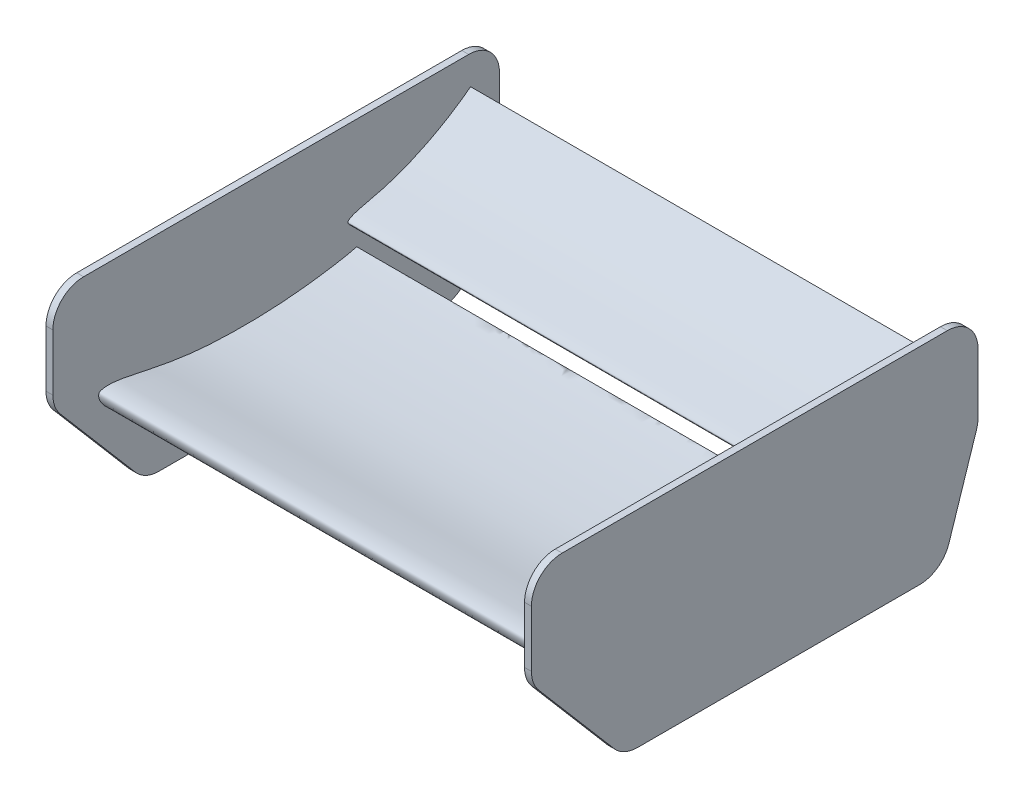
SolidWorks part; units mm, degrees
ref_plane "Front Plane" through (0, 0, 0) normal (0, 0, 1) x (1, 0, 0)
ref_plane "Top Plane" through (0, 0, 0) normal (0, 1, 0) x (1, 0, 0)
ref_plane "Right Plane" through (0, 0, 0) normal (1, 0, 0) x (0, 0, -1)
ref_plane "Soft Top Limit" through (0, 1174.6, 0) normal (0, 1, 0) x (1, 0, 0)
ref_plane "Soft Rear Limit" through (0, 0, -1192.975) normal (0, 0, 1) x (1, 0, 0)
ref_plane "Soft Right Limit" through (-501.65, 0, 0) normal (1, 0, 0) x (0, 0, -1)
ref_plane "Soft Left Limit" through (501.65, 0, 0) normal (1, 0, 0) x (0, 0, -1)
ref_plane "Soft Front Limit" through (0, 0, -165.1) normal (0, 0, 1) x (1, 0, 0)
ref_plane "Slant Limit" through (0, 528.6251, -619.2711) normal (0, -0.6492, 0.7606) x (1, 0, 0)
ref_plane "Bottom" through (0, 476.25, 0) normal (0, 1, 0) x (1, 0, 0)
ref_plane "Midplane" through (0, 0, 0) normal (1, 0, 0) x (0, 0, -1)
curve "Imported Airfoil Curve"
  spline degree 3 poles (0, 2520.0207, 6.126) (0, 2544.889, -1.81) (0, 2521.8965, 7.8839) (0, 2505.3253, 17.7145) (0, 2467.7144, 38.5723) (0, 2424.2142, 62.3813) (0, 2368.0949, 87.8078) (0, 2301.3729, 113.3478) (0, 2223.8362, 140.5377) (0, 2136.6129, 169.2441) (0, 2040.932, 199.097) (0, 1938.2341, 229.6055) (0, 1829.9414, 260.0781) (0, 1717.5266, 289.8586) (0, 1602.4273, 318.1375) (0, 1486.0259, 343.9752) (0, 1369.6902, 366.5754) (0, 1254.3666, 384.7865) (0, 1140.5393, 397.0034) (0, 1028.6357, 403.0127) (0, 919.0585, 402.9406) (0, 812.3986, 397.0375) (0, 709.2785, 385.5985) (0, 610.4299, 369.039) (0, 516.5862, 348.1086) (0, 428.5874, 323.3415) (0, 347.2653, 295.2055) (0, 273.332, 264.2656) (0, 207.4209, 231.0894) (0, 150.0337, 196.3024) (0, 101.596, 160.572) (0, 62.3674, 124.65) (0, 32.4977, 89.3959) (0, 12.0597, 55.6746) (0, 1.683, 26.6201) (0, -0.5567, 6.5526) (0, 0.5894, -3.9947) (0, 1.6947, -9.1451) (0, 2.8711, -12.4915) (0, 3.9449, -14.9776) (0, 4.8993, -16.669) (0, 5.9763, -18.2433) (0, 7.3264, -19.6365) (0, 8.8595, -20.9434) (0, 11.1868, -22.7306) (0, 14.6073, -24.7406) (0, 20.085, -27.4067) (0, 26.8353, -29.9257) (0, 44.6446, -35.1819) (0, 77.8093, -38.8998) (0, 130.2841, -38.2927) (0, 196.3018, -31.4611) (0, 276.2192, -18.4434) (0, 370.8288, 0.8611) (0, 480.7331, 24.811) (0, 605.9792, 50.0099) (0, 745.0759, 74.1542) (0, 895.4497, 95.0846) (0, 1053.6786, 110.004) (0, 1215.6439, 118.3392) (0, 1377.6893, 121.6348) (0, 1537.1174, 120.5125) (0, 1691.5141, 115.2051) (0, 1838.3121, 105.7388) (0, 1975.028, 93.0069) (0, 2099.5942, 78.4581) (0, 2210.5746, 63.1262) (0, 2306.3634, 48.0168) (0, 2387.2069, 33.7158) (0, 2449.0745, 22.0129) (0, 2499.1865, 10.4993) (0, 2520.0207, 6.126) (0, 2544.889, -1.81) (0, 2521.8965, 7.8839) knots -0.016237 -0.007308 -0.001841 0 0.001813 0.006911 0.014576 0.024172 0.035572 0.049013 0.064513 0.081849 0.100772 0.120997 0.142228 0.164173 0.186537 0.209023 0.231367 0.25332 0.274804 0.295858 0.316449 0.336531 0.356033 0.374893 0.39299 0.410197 0.426388 0.441459 0.455334 0.467938 0.479236 0.489204 0.497851 0.505194 0.511308 0.515097 0.516441 0.517273 0.51806 0.518436 0.518797 0.519154 0.519508 0.519887 0.520289 0.52116 0.522116 0.52372 0.525214 0.532575 0.542381 0.554776 0.569931 0.588005 0.609188 0.633329 0.660001 0.688743 0.718873 0.749543 0.780127 0.810209 0.839387 0.867183 0.893104 0.91676 0.937874 0.956199 0.971544 0.983763 0.992692 0.998159 1 1.001813 1.006911 1.014576 periodic
sketch "Airfoils Sketch" plane through (0, 0, 0) normal (1, 0, 0) x (0, 0, -1)
  line L0 (165.1, 1174.6) -> (165.1, 1060.6753) construction
  line L1 (165.1, 1060.6753) -> (663.9798, 476.25) construction
  line L2 (663.9798, 476.25) -> (1192.975, 476.25) construction
  line L3 (1192.975, 476.25) -> (1192.975, 1174.6) construction
  line L4 (1192.975, 1174.6) -> (165.1, 1174.6) construction
  line L5 (509.9361, 1174.6) -> (-509.9361, 1174.6) construction
  line L6 (165.1, 67.0076) -> (165.1, -67.0076) construction
  line L7 (364.7288, 826.8151) -> (873.8134, 230.4351) construction
  line L8 (279.3831, 476.25) -> (-279.3831, 476.25) construction
  line L9 (1192.975, 353.2696) -> (1192.975, -353.2696) construction
  line L10 (364.5896, 498.1423) -> (364.5896, 1393.8577) construction
  line L11 (897.9896, 508.5908) -> (897.9896, 1383.4092) construction
  line L12 (897.9896, 946) -> (364.5896, 946) construction
  line L13 (262.9896, 946) -> (1192.975, 946) construction
  line L14 (855.8887, 1048.5614) -> (904.1623, 945.0386) construction
  line L15 (1108.8736, 1167.1505) -> (1157.6222, 1062.6086) construction
  line L16 (1133.2479, 1114.8795) -> (880.0255, 996.8) construction
  line L17 (219.6255, 996.8) -> (1192.975, 996.8) construction
  line L21 (176.2614, 1047.6) -> (1192.975, 1047.6) construction
  spline S0 degree 3 poles (893.7912, 944.7229) (899.0172, 946.3778) (894.1843, 944.3529) (890.6998, 942.2962) (882.7919, 937.9336) (873.6459, 932.9541) (861.8492, 927.6408) (847.826, 922.3086) (831.5308, 916.6349) (813.2009, 910.6474) (793.0943, 904.4229) (771.5139, 898.0641) (748.7586, 891.7155) (725.138, 885.5141) (700.9544, 879.6292) (676.4985, 874.2577) (652.0578, 869.5659) (627.8318, 865.7954) (603.9228, 863.283) (580.4206, 862.0732) (557.4098, 862.1394) (535.0144, 863.4287) (513.3649, 865.8789) (492.6147, 869.4025) (472.9176, 873.8415) (454.4497, 879.0835) (437.3855, 885.0299) (421.8742, 891.5616) (408.0485, 898.5592) (396.0136, 905.8911) (385.8586, 913.417) (377.6374, 920.9787) (371.3813, 928.3959) (367.1052, 935.4868) (364.9396, 941.5929) (364.4786, 945.8081) (364.7242, 948.0225) (364.9587, 949.1035) (365.2073, 949.8057) (365.434, 950.3273) (365.6352, 950.682) (365.8621, 951.0121) (366.1463, 951.304) (366.4688, 951.5778) (366.9584, 951.952) (367.6776, 952.3725) (368.8291, 952.9298) (370.2479, 953.4556) (373.9902, 954.5511) (380.9564, 955.3164) (391.9757, 955.1645) (405.8359, 953.6991) (422.6123, 950.9282) (442.4709, 946.8302) (465.5393, 941.7496) (491.8288, 936.3995) (521.0273, 931.2645) (552.5956, 926.7991) (585.8161, 923.5923) (619.8244, 921.7664) (653.8518, 920.9989) (687.3317, 921.1602) (719.7569, 922.2028) (750.5884, 924.1223) (779.3042, 926.7322) (805.4694, 929.7293) (828.782, 932.8973) (848.9044, 936.0255) (865.8879, 938.991) (878.8853, 941.4197) (889.4141, 943.8142) (893.7912, 944.7229) (899.0172, 946.3778) (894.1843, 944.3529) knots -0.016237 -0.007308 -0.001841 0 0.001813 0.006911 0.014576 0.024172 0.035572 0.049013 0.064513 0.081849 0.100772 0.120997 0.142228 0.164173 0.186537 0.209023 0.231367 0.25332 0.274804 0.295858 0.316449 0.336531 0.356033 0.374893 0.39299 0.410197 0.426388 0.441459 0.455334 0.467938 0.479236 0.489204 0.497851 0.505194 0.511308 0.515097 0.516441 0.517273 0.51806 0.518436 0.518797 0.519154 0.519508 0.519887 0.520289 0.52116 0.522116 0.52372 0.525214 0.532575 0.542381 0.554776 0.569931 0.588005 0.609188 0.633329 0.660001 0.688743 0.718873 0.749543 0.780127 0.810209 0.839387 0.867183 0.893104 0.91676 0.937874 0.956199 0.971544 0.983763 0.992692 0.998159 1 1.001813 1.006911 1.014576 only from (897.9896, 946) to (897.9896, 946)
  spline S1 degree 3 poles (1131.5375, 1113.3438) (1133.6521, 1115.2864) (1131.806, 1113.2552) (1130.6071, 1111.5075) (1127.8187, 1107.6858) (1124.5791, 1103.2972) (1120.1551, 1098.1634) (1114.6782, 1092.5276) (1108.1983, 1086.2269) (1100.822, 1079.3267) (1092.6546, 1071.9207) (1083.8174, 1064.1247) (1074.4201, 1056.0734) (1064.5795, 1047.9005) (1054.4014, 1039.7532) (1043.9805, 1031.7893) (1033.4164, 1024.1515) (1022.7502, 1016.9986) (1011.956, 1010.5131) (1001.0665, 1004.736) (990.1279, 999.6735) (979.2106, 995.3279) (968.3905, 991.6985) (957.7597, 988.7777) (947.4262, 986.5247) (937.4984, 984.925) (928.0811, 983.9704) (919.2715, 983.6375) (911.1589, 983.8989) (903.8225, 984.7154) (897.3355, 986.0401) (891.7587, 987.81) (887.1468, 989.9462) (883.547, 992.3659) (881.1672, 994.7853) (880.0153, 996.6843) (879.6417, 997.7899) (879.5137, 998.355) (879.4763, 998.7434) (879.4684, 999.0412) (879.4854, 999.2542) (879.52, 999.4611) (879.5903, 999.6626) (879.6829, 999.864) (879.8324, 1000.15) (880.0808, 1000.5088) (880.5041, 1001.0283) (881.0612, 1001.592) (882.5953, 1002.9405) (885.733, 1004.8459) (890.9978, 1007.2132) (897.9021, 1009.5858) (906.4798, 1011.9841) (916.8145, 1014.4348) (928.8905, 1017.1296) (942.5554, 1020.4095) (957.5536, 1024.4354) (973.5286, 1029.3038) (990.0094, 1035.1356) (1006.5584, 1041.7972) (1022.8822, 1048.9655) (1038.7405, 1056.4536) (1053.903, 1064.1266) (1068.1148, 1071.863) (1081.1694, 1079.4589) (1092.9274, 1086.674) (1103.2934, 1093.3387) (1112.1536, 1099.2783) (1119.5597, 1104.4457) (1125.1924, 1108.476) (1129.6607, 1111.9435) (1131.5375, 1113.3438) (1133.6521, 1115.2864) (1131.806, 1113.2552) knots -0.016237 -0.007308 -0.001841 0 0.001813 0.006911 0.014576 0.024172 0.035572 0.049013 0.064513 0.081849 0.100772 0.120997 0.142228 0.164173 0.186537 0.209023 0.231367 0.25332 0.274804 0.295858 0.316449 0.336531 0.356033 0.374893 0.39299 0.410197 0.426388 0.441459 0.455334 0.467938 0.479236 0.489204 0.497851 0.505194 0.511308 0.515097 0.516441 0.517273 0.51806 0.518436 0.518797 0.519154 0.519508 0.519887 0.520289 0.52116 0.522116 0.52372 0.525214 0.532575 0.542381 0.554776 0.569931 0.588005 0.609188 0.633329 0.660001 0.688743 0.718873 0.749543 0.780127 0.810209 0.839387 0.867183 0.893104 0.91676 0.937874 0.956199 0.971544 0.983763 0.992692 0.998159 1 1.001813 1.006911 1.014576 only from (1133.2479, 1114.8795) to (1133.2479, 1114.8795)
  dimension "D1" = 533.4
  dimension "D2" = 228.6
  dimension "D3" = 0
  dimension "D4" = 101.6
  dimension "D5" = 279.4
  dimension "D6" = 177.8
  dimension "D7" = 25
  dimension "D8" = 660.4
extrude "Extruded Airfoils" add sketch "Airfoils Sketch" along normal offset from surface (487.45 mm away) 14.2 up to plane "Soft Left Limit"
sketch "Endplate Sketch" plane through (501.65, 0, 0) normal (1, 0, 0) x (0, 0, -1)
  line L6 (333.4477, 1174.6) -> (1129.475, 1174.6)
  line L7 (1192.975, 1174.6) -> (165.1, 1174.6) construction
  line L8 (1192.975, 1111.1) -> (1192.975, 986.6717)
  line L9 (1192.975, 476.25) -> (1192.975, 1174.6) construction
  line L11 (1189.8464, 966.9854) -> (1132.8969, 792.34)
  line L12 (1072.5255, 748.5263) -> (489.1772, 748.5263)
  line L19 (440.8805, 770.7991) -> (285.151, 953.2323)
  line L26 (269.9477, 994.4595) -> (269.9477, 1111.1)
  line L28 (165.1, 1060.6753) -> (663.9798, 476.25) construction
  arc A12 (1129.475, 1174.6) -> (1192.975, 1111.1) centre (1129.475, 1111.1) cw
  arc A13 (1192.975, 986.6717) -> (1189.8464, 966.9854) centre (1129.475, 986.6717) cw
  arc A14 (1132.8969, 792.34) -> (1072.5255, 748.5263) centre (1072.5255, 812.0263) cw
  arc A15 (489.1772, 748.5263) -> (440.8805, 770.7991) centre (489.1772, 812.0263) cw
  arc A16 (285.151, 953.2323) -> (269.9477, 994.4595) centre (333.4477, 994.4595) cw
  arc A17 (333.4477, 1174.6) -> (269.9477, 1111.1) centre (333.4477, 1111.1) ccw
  point P16 (1192.975, 1174.6)
  point P19 (1192.975, 976.5799)
  point P29 (269.9477, 1174.6)
  dimension "D1" = 63.5
extrude "Extruded Endplate" add sketch "Endplate Sketch" against normal up to surface (14.2 mm away)
mirror "Mirror" about plane through (0, 0, 0) normal (1, 0, 0) of bodies 106
ref_point "Point2"
ref_plane "Plane1" through (0, 1143, 0) normal (0, 1, 0) x (1, 0, 0)
sketch "Sketch1" plane through (0, 1143, 0) normal (0, 1, 0) x (1, 0, 0)
  circle A0 centre (0, 139.7) radius 2000 construction
  dimension "D1" = 4000
ref_plane "Plane2" through (0, 0, 0) normal (0, 1, 0) x (1, 0, 0)
sketch "Sketch2" plane through (0, 0, 0) normal (1, 0, 0) x (0, 0, -1)
  line L0 (55, 0) -> (-55, 0) construction
  line L1 (-2459.9326, 1300) -> (2139.7, 1300) construction
  line L2 (-2459.9326, 1300) -> (-2459.9326, 0) construction
  line L3 (-2459.9326, 0) -> (2139.7, 0) construction
  line L4 (2139.7, 1300) -> (2139.7, 0) construction
  line L5 (2139.7, 1300) -> (2139.7, 1143) construction
  point P6 (0, 0)
  dimension "D1" = 1300
